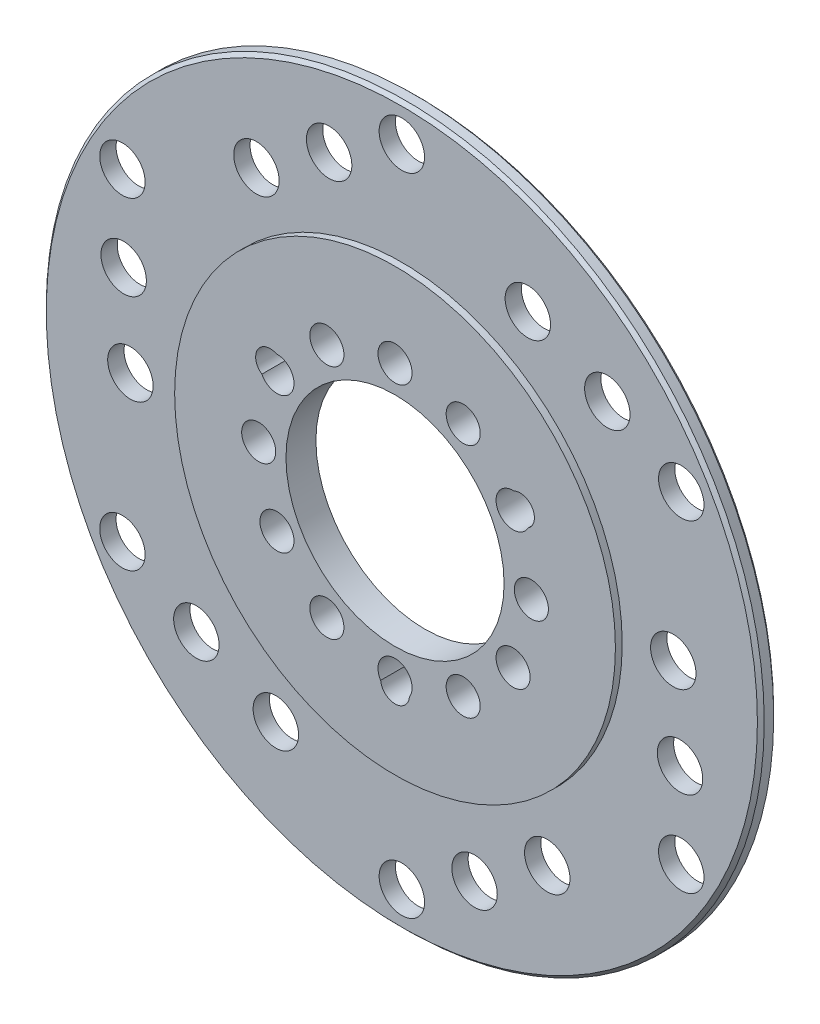
SolidWorks part; units mm, degrees
ref_plane "Front Plane" through (0, 0, 0) normal (0, 0, 1) x (1, 0, 0)
ref_plane "Top Plane" through (0, 0, 0) normal (0, 1, 0) x (1, 0, 0)
ref_plane "Right Plane" through (0, 0, 0) normal (1, 0, 0) x (0, 0, -1)
sketch "Sketch2" plane through (0, 0, 0) normal (0, 0, 1) x (1, 0, 0)
  circle A0 centre (0, 0) radius 79
  circle A1 centre (0, 0) radius 24
  dimension "D1" = 158
  dimension "D2" = 48
extrude "Boss-Extrude1" add sketch "Sketch2" along normal blind 3.59
sketch "Sketch5" plane through (0, 0, 3.59) normal (0, 0, 1) x (1, 0, 0)
  circle A0 centre (0, 0) radius 48.5
  circle A1 centre (0, 0) radius 24 construction
  circle A2 centre (0, 0) radius 24
  dimension "D1" = 97
extrude "Boss-Extrude2" add sketch "Sketch5" along normal blind 1.5 and the other way blind 5.09
sketch "Sketch3" plane through (0, 0, 3.59) normal (0, 0, 1) x (1, 0, 0)
  circle A0 centre (0, -30) radius 3.75
  circle A1 centre (-15, -25.9808) radius 3.75
  circle A2 centre (-25.9808, -15) radius 3.75
  circle A3 centre (-30, 0) radius 3.75
  circle A4 centre (-25.9808, 15) radius 3.75
  circle A5 centre (-15, 25.9808) radius 3.75
  circle A6 centre (0, 30) radius 3.75
  circle A7 centre (15, 25.9808) radius 3.75
  circle A8 centre (25.9808, 15) radius 3.75
  circle A9 centre (30, 0) radius 3.75
  circle A10 centre (25.9808, -15) radius 3.75
  circle A11 centre (15, -25.9808) radius 3.75
  point P26 (0, 0)
  dimension "D2" = 7.5
  dimension "D3" = 30
  dimension "D1" = 12
extrude "Cut-Extrude2" cut sketch "Sketch3" against normal through all and the other way through all
sketch "Sketch6" plane through (0, 0, 3.59) normal (0, 0, 1) x (1, 0, 0)
  line L0 (0, 0) -> (0, -140.2708) construction
  circle A0 centre (0, -71) radius 5
  circle A1 centre (16, -61.4512) radius 5
  circle A2 centre (32, -50.4943) radius 5
  circle A3 centre (0, 0) radius 79 construction
  circle A6 centre (-61.4878, -35.5) radius 5
  circle A7 centre (-61.4878, 35.5) radius 5
  circle A8 centre (0, 71) radius 5
  circle A9 centre (61.4878, 35.5) radius 5
  circle A10 centre (61.4878, -35.5) radius 5
  circle A11 centre (-45.2183, -44.582) radius 5
  circle A12 centre (-61.2183, 16.8692) radius 5
  circle A13 centre (-16, 61.4512) radius 5
  circle A14 centre (45.2183, 44.582) radius 5
  circle A15 centre (61.2183, -16.8692) radius 5
  circle A16 centre (-27.7293, -52.9599) radius 5
  circle A17 centre (-59.7293, -2.4657) radius 5
  circle A18 centre (-32, 50.4943) radius 5
  circle A19 centre (27.7293, 52.9599) radius 5
  circle A20 centre (59.7293, 2.4657) radius 5
  point P27 (0, 0)
  point P35 (0, 0)
  point P45 (0, 0)
  dimension "D2" = 10
  dimension "D1" = 71
  dimension "D3" = 16
  dimension "D4" = 16
  dimension "D5" = 6
  dimension "D6" = 6
  dimension "D7" = 6
extrude "Cut-Extrude3" cut sketch "Sketch6" against normal through all
chamfer "Chamfer1" distance 0.75 angle 45 2 edges at (79, 0, 0) (79, 0, 3.59)
hole_wizard "1/4 (0.25) Diameter Hole2" positions "Sketch13" profile "Sketch12" hole size "1/4" standard "ANSI Inch" end condition through all
sketch "Sketch13" plane through (0, 0, 5.09) normal (0, 0, 1) x (1, 0, 0)
  circle A0 centre (0, 0) radius 31.75
  point P5 (0, -31.75)
  point P12 (-27.4963, 15.875)
  point P13 (27.4963, 15.875)
  dimension "D1" = 63.5
  dimension "D2" = 3
sketch "Sketch12" plane through (27.4963, 15.875, 5.09) normal (1, 0, 0) x (0, -1, 0)
  line L0 (0, 0) -> (0, 6.59)
  line L1 (0, 6.59) -> (3.175, 6.59)
  line L2 (3.175, 6.59) -> (3.175, 0)
  line L5 (3.175, 0) -> (0, 0)
  line L11 (0, -6.35) -> (0, 107.95) construction
  dimension "Thru Hole Dia." = 6.35
  dimension "Thru Hole Depth" = 6.59
